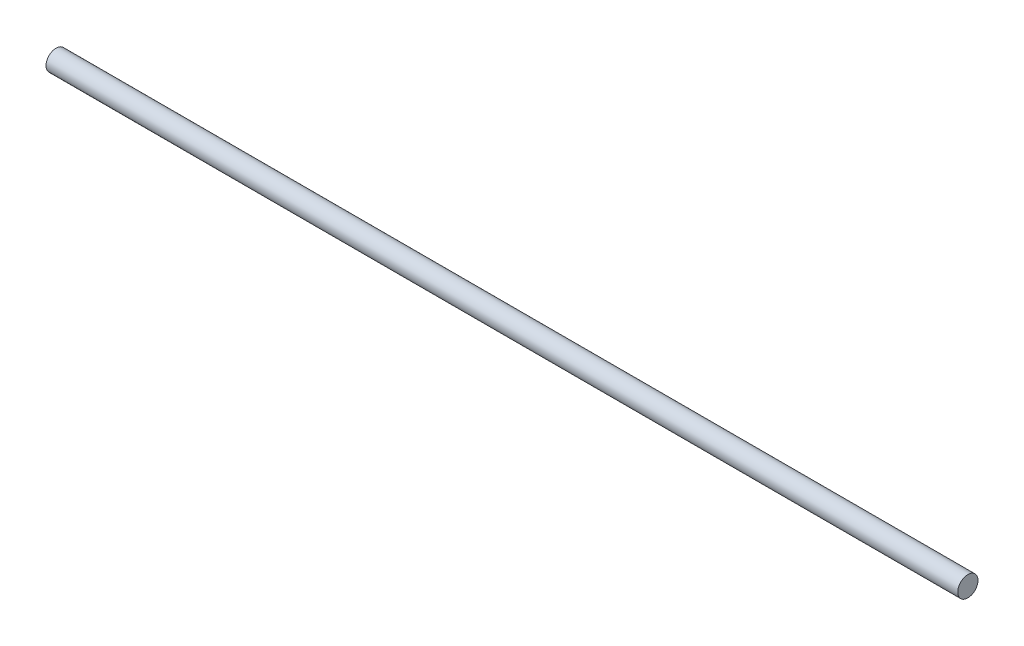
SolidWorks part; units mm, degrees
ref_plane "Front" through (0, 0, 0) normal (0, 0, 1) x (1, 0, 0)
ref_plane "Top" through (0, 0, 0) normal (0, 1, 0) x (1, 0, 0)
ref_plane "Right" through (0, 0, 0) normal (1, 0, 0) x (0, 0, -1)
sketch "Sketch1" plane through (0, 0, 0) normal (1, 0, 0) x (0, 0, -1)
  circle A0 centre (0, 0) radius 4.7625
  dimension "D1" = 9.525
extrude "Extrude1" add sketch "Sketch1" along normal mid plane 428.625
